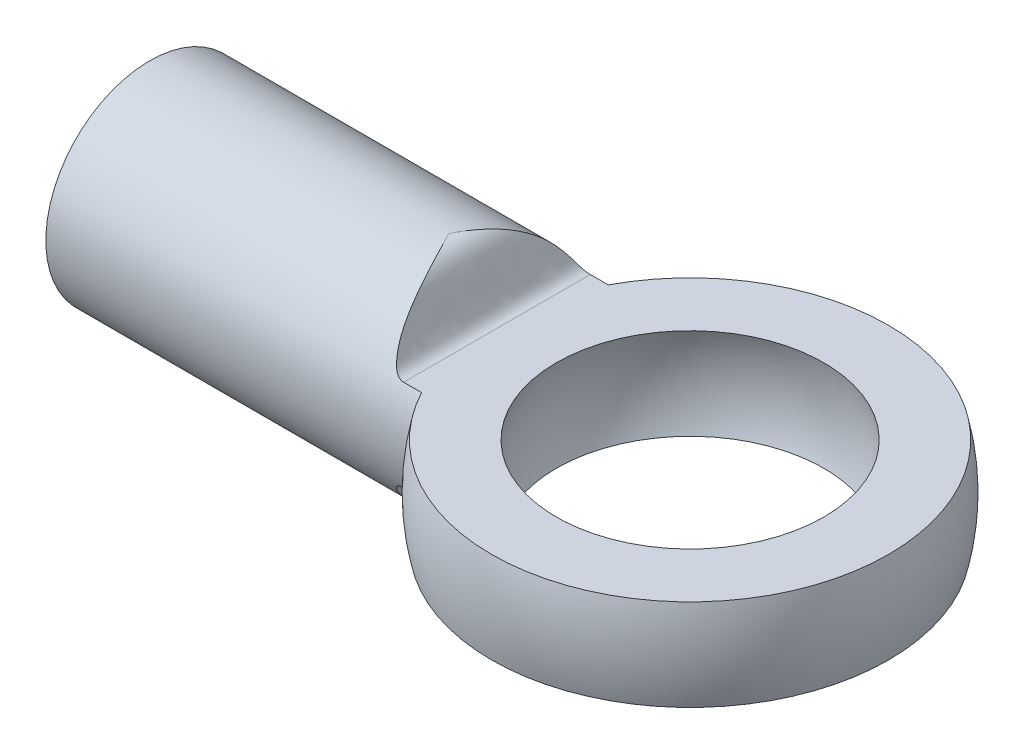
SolidWorks part; units mm, degrees
ref_plane "Front Plane" through (0, 0, 0) normal (0, 0, 1) x (1, 0, 0)
ref_plane "Top Plane" through (0, 0, 0) normal (0, 1, 0) x (1, 0, 0)
ref_plane "Right Plane" through (0, 0, 0) normal (1, 0, 0) x (0, 0, -1)
sketch "Sketch2" plane through (0, 0, 0) normal (0, 0, 1) x (1, 0, 0)
  line L0 (0, 4.0719) -> (0, -4.858) construction
  line L1 (3.2171, 1.1) -> (4.7749, 1.1)
  line L2 (3.2171, -1.1) -> (4.7749, -1.1)
  line L3 (0, 0) -> (5.481, 0) construction
  arc A0 (3.2171, 1.1) -> (3.2171, -1.1) centre (0, 0) cw
  arc A1 (4.7749, 1.1) -> (4.7749, -1.1) centre (0, 0) cw
  point P8 (3.4, 0)
  dimension "D1" = 3.4
  dimension "D2" = 4.9
  dimension "D3" = 2.2
revolve "Revolve1" add sketch "Sketch2" angle 360 about L0
sketch "Sketch3" plane through (0, 0, 0) normal (0, 1, 0) x (1, 0, 0)
  line L0 (-1.07, 0) -> (-15.8552, 0) construction
  line L1 (-13, 1.5) -> (-5.9749, 1.5)
  line L2 (-4.0682, 2.5) -> (-13, 2.5)
  line L3 (-13, 2.5) -> (-13, 1.5)
  line L4 (-5.9749, 1.5) -> (-5.9749, 0)
  line L5 (-5.9749, 0) -> (-4.7749, 0)
  circle A0 centre (0, 0) radius 4.7749 construction
  arc A2 (-4.7749, 0) -> (-4.0682, 2.5) centre (0, 0) cw
  dimension "D1" = 3
  dimension "D2" = 5
  dimension "D4" = 1.2
revolve "Revolve2" add sketch "Sketch3" angle 360 about L0
sketch "Sketch5" plane through (0, 0, 0) normal (0, 0, 1) x (1, 0, 0)
  line L1 (-1.7062, 0) -> (-6.8465, 0) construction
  line L2 (-4.0682, 2.5) -> (-13, 2.5) construction
  line L3 (-4.2835, 1.1) -> (-4.1451, 1.1) construction
  line L4 (-5.8023, 2.5) -> (-3.7409, 2.5)
  line L5 (-3.7409, 2.5) -> (-3.7409, 1.1)
  line L6 (4.7749, 1.1) -> (-4.2143, 1.1) construction
  line L7 (-3.7409, 1.1) -> (-4.6465, 1.1)
  line L8 (-6.063, 2.5) -> (-5.521, 2.5) construction
  line L9 (-3.7409, -1.1) -> (-4.6465, -1.1)
  line L10 (-5.8023, -2.5) -> (-3.7409, -2.5)
  line L11 (-3.7409, -2.5) -> (-3.7409, -1.1)
  spline S0 degree 3 poles (-4.6465, 1.1) (-4.8085, 1.1) (-5.0373, 1.4525) (-5.1795, 2.0191) (-5.4725, 2.5) (-5.8023, 2.5) knots 0 0 0 0 0.209972 0.594974 1 1 1 1
  spline S1 degree 3 poles (-4.6465, -1.1) (-4.8085, -1.1) (-5.0373, -1.4525) (-5.1795, -2.0191) (-5.4725, -2.5) (-5.8023, -2.5) knots 0 0 0 0 0.209972 0.594974 1 1 1 1
extrude "Cut-Extrude1" cut sketch "Sketch5" against normal up to next and the other way up to next
